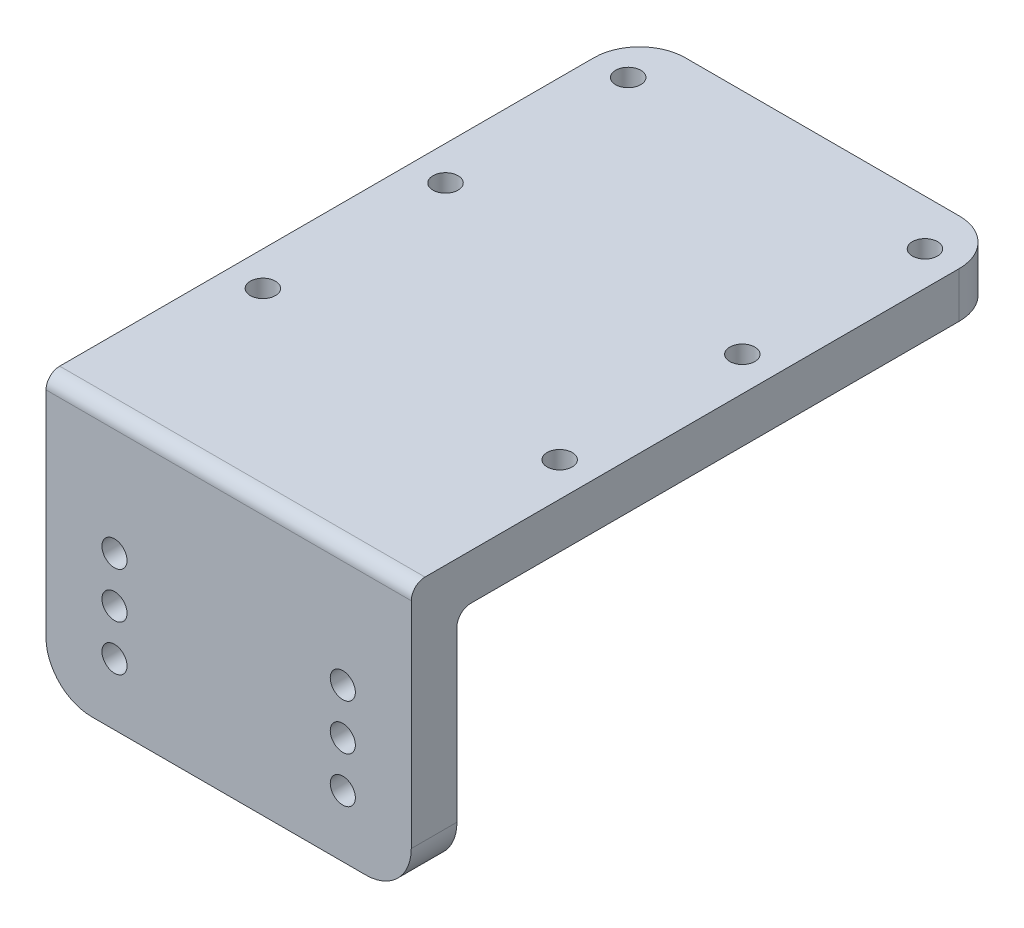
SolidWorks part; units mm, degrees
ref_plane "Front Plane" through (0, 0, 0) normal (0, 0, 1) x (1, 0, 0)
ref_plane "Top Plane" through (0, 0, 0) normal (0, 1, 0) x (1, 0, 0)
ref_plane "Right Plane" through (0, 0, 0) normal (1, 0, 0) x (0, 0, -1)
sketch "Sketch1" plane through (0, 0, 0) normal (0, 0, 1) x (1, 0, 0)
  line L1 (-40, 30) -> (40, 30)
  line L2 (-40, 30) -> (-40, -30)
  line L3 (-40, -30) -> (40, -30)
  line L4 (40, 30) -> (40, -30)
  line L5 (-40, 30) -> (40, -30) construction
  line L6 (-40, -30) -> (40, 30) construction
  point P0 (0, 0)
  dimension "D1" = 80
  dimension "D2" = 60
extrude "Boss-Extrude1" add sketch "Sketch1" along normal blind 10
sketch "Sketch2" plane through (0, 30, 0) normal (0, 1, 0) x (1, 0, 0)
  line L0 (40, -10) -> (-40, -10) construction
  line L1 (-40, 120) -> (40, 120)
  line L2 (-40, 120) -> (-40, -10)
  line L3 (-40, -10) -> (40, -10)
  line L4 (40, 120) -> (40, -10)
  line L5 (-40, 120) -> (40, -10) construction
  line L6 (-40, -10) -> (40, 120) construction
  point P0 (0, 55)
  dimension "D1" = 130
  dimension "D2" = 80
extrude "Boss-Extrude2" add sketch "Sketch2" against normal blind 10
sketch "Sketch3" plane through (0, 0, 0) normal (0, 0, -1) x (-1, 0, 0)
  line L0 (40, -30) -> (-40, -30) construction
  circle A0 centre (-25, -16.5) radius 2.75
  circle A1 centre (25, -16.5) radius 2.75
  circle A2 centre (-25, -6.5) radius 2.75
  circle A3 centre (25, -6.5) radius 2.75
  circle A4 centre (-25, 3.5) radius 2.75
  circle A5 centre (25, 3.5) radius 2.75
  dimension "D2" = 5.5
  dimension "D1" = 13.5
  dimension "D3" = 25
  dimension "D4" = 25
  dimension "D5" = 10
  dimension "D6" = 2
extrude "Cut-Extrude1" cut sketch "Sketch3" against normal up to next
sketch "Sketch4" plane through (0, 20, 0) normal (0, -1, 0) x (1, 0, 0)
  line L0 (-40, -120) -> (-40, 0) construction
  line L1 (40, 0) -> (40, -120) construction
  line L2 (-40, 0) -> (40, 0) construction
  circle A0 centre (-32.5, -110) radius 2.75
  circle A1 centre (32.5, -110) radius 2.75
  circle A3 centre (-32.5, -70) radius 2.75
  circle A4 centre (32.5, -70) radius 2.75
  circle A5 centre (-32.5, -30) radius 2.75
  circle A6 centre (32.5, -30) radius 2.75
  dimension "D1" = 5.5
  dimension "D2" = 7.5
  dimension "D3" = 7.5
  dimension "D4" = 40
  dimension "D5" = 70
  dimension "D6" = 40
extrude "Cut-Extrude2" cut sketch "Sketch4" against normal up to next
sketch "Sketch5" plane through (0, 0, 0) normal (0, 0, -1) x (-1, 0, 0)
  line L0 (-40, 20) -> (40, 20) construction
  line L1 (-5, -30) -> (5, -30)
  line L2 (-5, -30) -> (-5, 20)
  line L3 (-5, 20) -> (5, 20)
  line L4 (5, -30) -> (5, 20)
  line L5 (-5, -30) -> (5, 20) construction
  line L6 (-5, 20) -> (5, -30) construction
  line L7 (40, -30) -> (-40, -30) construction
  point P0 (0, -5)
  dimension "D1" = 10
extrude "Boss-Extrude3" add sketch "Sketch5" along normal up to surface (120 mm away) up to face at (0, 25, -120)
sketch "Sketch6" plane through (-5, 0, 0) normal (-1, 0, 0) x (0, 0, 1)
  line L0 (-120, 20) -> (-120, -30)
  line L1 (-120, -30) -> (0, -30)
  line L2 (0, -30) -> (-120, 20)
extrude "Cut-Extrude3" cut sketch "Sketch6" against normal up to next
fillet "Fillet1" radius 10 4 edges at (-40, 25, -120) (-40, -30, 5) (40, -30, 5) (40, 25, -120)
fillet "Fillet2" radius 3 1 edges at (0, 30, 10)
fillet "Fillet3" radius 3 6 edges at (5, 20, -60) (-5, 20, -60) (-22.5, 20, 0) (-5, -5, 0) (5, -5, 0) (22.5, 20, 0)
